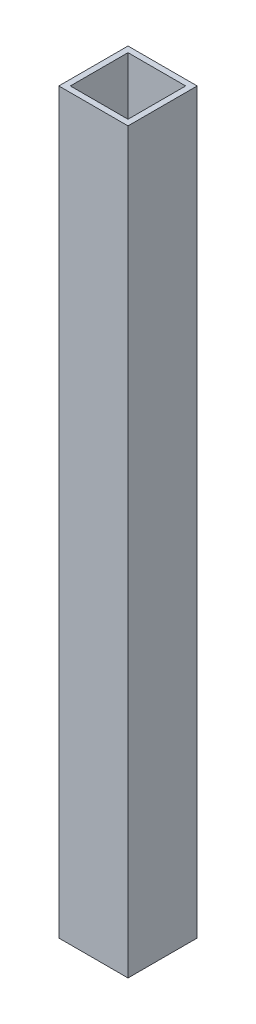
SolidWorks part; units mm, degrees
ref_plane "Front" through (0, 0, 0) normal (0, 0, 1) x (1, 0, 0)
ref_plane "Top" through (0, 0, 0) normal (0, 1, 0) x (1, 0, 0)
ref_plane "Right" through (0, 0, 0) normal (1, 0, 0) x (0, 0, -1)
sketch "Sketch1" plane through (0, 0, 0) normal (0, 1, 0) x (1, 0, 0)
  line L1 (0, 0) -> (19.05, 0)
  line L2 (0, 0) -> (0, 19.05)
  line L3 (0, 19.05) -> (19.05, 19.05)
  line L4 (19.05, 0) -> (19.05, 19.05)
  line L5 (0, 0) -> (19.05, 19.05) construction
  line L6 (0, 19.05) -> (19.05, 0) construction
  line L7 (1.5875, 1.5875) -> (17.4625, 1.5875)
  line L8 (1.5875, 1.5875) -> (1.5875, 17.4625)
  line L9 (1.5875, 17.4625) -> (17.4625, 17.4625)
  line L10 (17.4625, 1.5875) -> (17.4625, 17.4625)
  line L11 (1.5875, 1.5875) -> (17.4625, 17.4625) construction
  line L12 (1.5875, 17.4625) -> (17.4625, 1.5875) construction
  point P4 (9.525, 9.525)
  point P5 (9.525, 9.525)
  dimension "D1" = 1.5875
  dimension "D2" = 1.5875
  dimension "D3" = 19.05
extrude "Boss-Extrude1" add sketch "Sketch1" along normal blind 203.2
